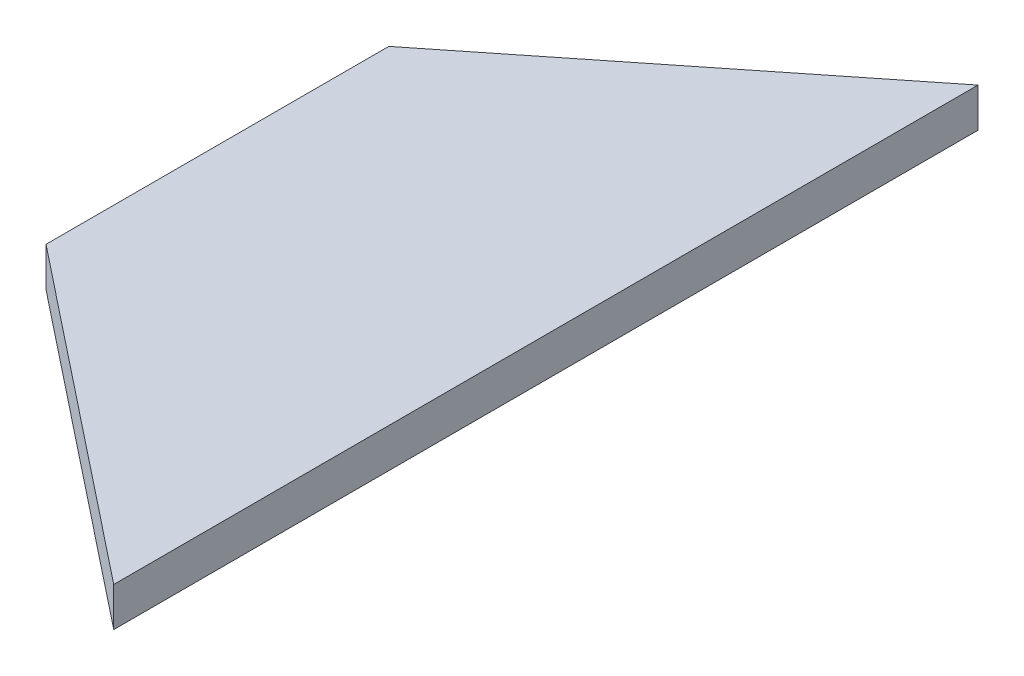
SolidWorks part; units mm, degrees
ref_plane "Front Plane" through (0, 0, 0) normal (0, 0, 1) x (1, 0, 0)
ref_plane "Top Plane" through (0, 0, 0) normal (0, 1, 0) x (1, 0, 0)
ref_plane "Right Plane" through (0, 0, 0) normal (1, 0, 0) x (0, 0, -1)
sketch "Sketch1" plane through (0, 0, 0) normal (0, 1, 0) x (1, 0, 0)
  line L1 (0, 0) -> (263.3435, 0)
  line L2 (0, 0) -> (0, 204.1914)
  line L3 (0, 204.1914) -> (263.3435, 204.1914)
  line L4 (263.3435, 0) -> (263.3435, 204.1914)
  line L5 (0, 0) -> (263.3435, 204.1914) construction
  line L6 (0, 204.1914) -> (263.3435, 0) construction
  point P4 (131.6717, 102.0957)
  dimension "D1" = 263.3435
  dimension "D2" = 204.1914
extrude "Boss-Extrude1" add sketch "Sketch1" along normal blind 4.6
sketch "Sketch2" plane through (0, 4.6, 0) normal (0, 1, 0) x (1, 0, 0)
  line L5 (263.3435, 21.7914) -> (248.8375, 4.5493)
  line L6 (224.7296, 52.4414) -> (191.0769, 52.4414)
  line L7 (191.0769, 52.4414) -> (191.0769, 92.7414)
  line L8 (224.7296, 92.7414) -> (191.0769, 92.7414)
  line L9 (224.7296, 52.4414) -> (224.7296, 92.7414)
  line L11 (263.3435, 21.7914) -> (248.8375, 4.5493)
  line L12 (263.3036, 123.4388) -> (199.2353, 199.5914)
  line L13 (263.3036, 123.4388) -> (224.7296, 92.7414)
  line L14 (224.7296, 52.4414) -> (263.3435, 21.7914)
  line L15 (263.3036, 123.4388) -> (263.3435, 21.7914)
  point P0 (263.3435, 21.7914)
  point P8 (263.3435, 21.7914)
  point P9 (263.3435, 123.3914)
extrude "Cut-Extrude1" cut sketch "Sketch2" against normal through all flip side to cut contours L15 L13 L9 L14
equation "\"MDF\"= 4.8mm"
equation "\"Foamcore\"= 4.6mm"
equation "\"GMaterial\"= \"MDF\""
equation "\"PCB\" = 1.6mm"
equation "\"BaseWidth\" = 10in"
equation "\"SkidLength\" = 1in"
equation "\"SkidClearance\" = 0.4in"
equation "\"MotorMountLength\" = 2in"
equation "\"MotorMountWidth\" = \"GMaterial\""
equation "\"MotorMountHeight\" = 2.25in"
equation "\"UnoStackWidth\" = 77.4mm"
equation "\"UnoStackLength\" = 79.8mm"
equation "\"UnoStackHeight\" = 34.2mm"
equation "\"TallHexRiserHeight\" = 22.2mm"
equation "\"PingPongBallSize\" = 40mm"
equation "\"BarrelLength\" = 9in"
equation "\"BarrelSize\" = \"PingPongBallSize\""
equation "\"PlatformLength\" = 4in"
equation "\"PlatformWidth\" = 6in"
equation "\"WheelDiameter\"=2.99213"
equation "\"ServoMountHeight\"=2.49223"
equation "\"ServoGearHeight\" = 0.95330261in"
equation "\"ServoMountLength\"= 1.53774"
equation "\"PivotHoleRadius\"= 0.616358"
equation "\"PlatformMountHeight\" = 3.19"
equation "\"TensionOffSet\"= .3mm"
equation "\"MotorMountWedge\"=0.333333"
equation "\"LaserCutterOffset\"= .3mm"
equation "\"BumperWidth\"=11"
equation "\"PitcherWheelCompression\" = 2.5mm"
equation "\"BarrelToHopperDistance\" = 0.5405in"
equation "\"PitchingWheelWidth\" = 26.2mm"
equation "\"PitchingWheelDiameter\" = 65.5mm"
equation "\"PitchingWheelMountOffset\" = 8.4mm"
equation "\"PitchingWheelInnerDiameter\" = 45.5mm"
equation "\"PitchingWheelBoltShoulder\" = 4.5mm"
equation "\"BrassCouplingLength\" = 18mm"
equation "\"PitchingMotorHeight\" = 57.0mm"
equation "\"PitchingMotorShaftTopHeight\" = \"PitchingMotorHeight\" - 44.1mm"
equation "\"PitchingMotorBodyHeight\" = 38mm"
equation "\"PitchingMotorTopShoulderHeight\" = 40.6mm - \"PitchingMotorBodyHeight\" "
equation "\"PitchingMotorBottomShoulderHeight\" = 40.2mm - \"PitchingMotorBodyHeight\""
equation "\"PitchingMotorBottomShaftHeight\" = \"PitchingMotorHeight\" - \"PitchingMotorShaftTopHeight\" - \"PitchingMotorTopShoulderHeight\" - \"PitchingMotorBodyHeight\" - \"PitchingMotorBottomShoulderHeight\""
equation "\"PitchingMotorShaftDiameter\" = 2.2mm"
equation "\"PitchingMotorBodyDiameter\" = 27.4mm"
equation "\"PitchingMotorTopShoulderDiameter\" = 9.8mm"
equation "\"PitchingMotorBottomShoulderDiameter\" = 9.8mm"
equation "\"BrassCouplingHexSize\" = 12mm"
equation "\"BrassCouplingBoreSize\" = 3.17mm"
equation "\"PitchingMotorMountingHoleDistance\" = 16mm"
equation "\"Acrylic\" = 4.4mm"
equation "\"PitchingMotorDistance\" = \"PitchingWheelDiameter\" + \"PingPongBallSize\" - \"PitcherWheelCompression\"*2"
equation "\"PitchingMotorPlatformOffset\"=1"
equation "\"ServoPlatformOffset\"=1.64173"
equation "\"BallBearingDiameter\" = 22mm"
equation "\"BallBearingWidth\" = 9mm"
equation "\"BallBearingHexShoulder\" = 9mm - 5.9mm"
equation "\"BallBearingHexSize\" = .36in"
equation "\"PlatformMountFootLength\"=0.857143"
equation "\"WheelWidth\"= 26mm"
equation "\"ServoMountReductionBackHeight\"=2.25"
equation "\"PlatformBottomWidthThird\" =  0.857143in"
equation "\"PlatformMountBackReductionHeight\"= 2.5in"
equation "\"PlatformMountBackReductionWidth\"= 3/7in"
equation "\"PlatformMountFrontReductionWidth\" =  1.46226in"
equation "\"PlatformMountFrontReductionHeight\" = 2.5in"
equation "\"HopperLongWallLength\" = 8.646in"
equation "\"HopperShortWallLength\" = 0.9571in"
equation "\"HopperHeight\" = 3.50in - \"Foamcore\""
equation "\"HoperLongSlantLength\" = 7.064in"
equation "\"HopperBottomTemplateWidth\" = 8.03903165in"
equation "\"HopperBottomTemplateLength\" = 10.367854in"
equation "\"D1@Sketch1\"=\"HopperBottomTemplateLength\""
equation "\"D2@Sketch1\"=\"HopperBottomTemplateWidth\""
equation "\"D1@Boss-Extrude1\"=\"Foamcore\""
